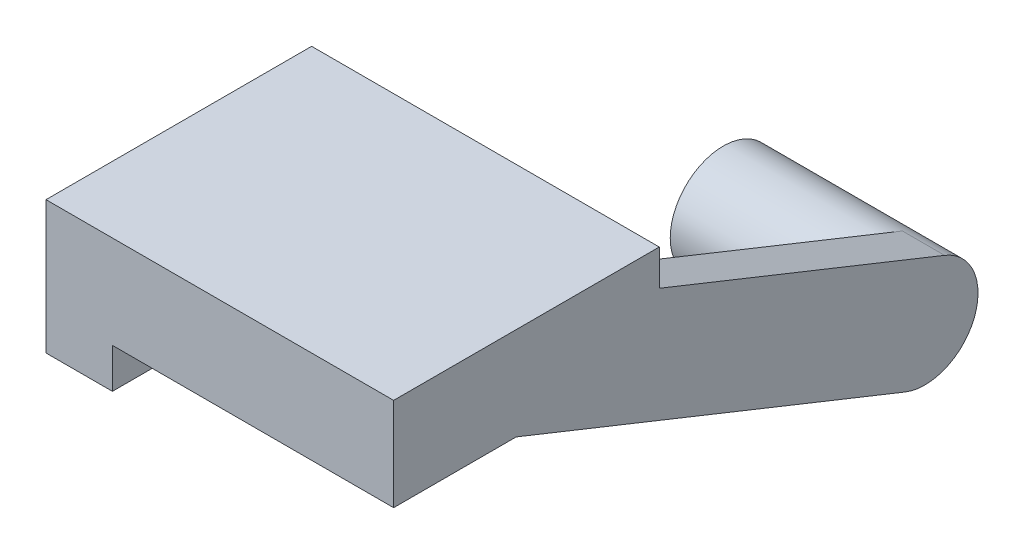
SolidWorks part; units mm, degrees
material "ABS"
ref_plane "Front Plane" through (0, 0, 0) normal (0, 0, 1) x (1, 0, 0)
ref_plane "Top Plane" through (0, 0, 0) normal (0, 1, 0) x (1, 0, 0)
ref_plane "Right Plane" through (0, 0, 0) normal (1, 0, 0) x (0, 0, -1)
sketch "Sketch1" plane through (0, 0, 0) normal (1, 0, 0) x (0, 0, -1)
  line L0 (-5, 0) -> (5, 0) construction
  line L1 (-10, -5) -> (10, -5)
  line L2 (-10, -5) -> (-10, 5)
  line L3 (-10, 5) -> (10, 5)
  line L4 (10, -5) -> (10, 5)
  line L5 (-10, -5) -> (10, 5) construction
  line L6 (-10, 5) -> (10, -5) construction
  circle A0 centre (-5, 0) radius 1.65
  circle A1 centre (5, 0) radius 1.65
  point P0 (0, 0)
  dimension "D1" = 3.3
  dimension "D2" = 10
  dimension "D3" = 20
  dimension "D4" = 10
extrude "Boss-Extrude1" add sketch "Sketch1" along normal blind 5
sketch "Sketch2" plane through (5, 0, 0) normal (1, 0, 0) x (0, 0, -1)
  line L1 (10, -5) -> (10, 5) construction
  line L2 (-10, 5) -> (10, 5)
  line L3 (-10, 5) -> (-10, -2)
  line L4 (-10, -2) -> (10, -2)
  line L13 (10, 5) -> (10, -2)
  line L14 (-10, -5) -> (10, -5) construction
  dimension "D1" = 3
extrude "Boss-Extrude2" add sketch "Sketch2" along normal blind 18
sketch "Sketch3" plane through (23, 0, 0) normal (1, 0, 0) x (0, 0, -1)
  line L0 (10, -2) -> (10, 5) construction
  line L1 (-10, 5) -> (34, 5) construction
  line L2 (-10, 5) -> (-10, -14) construction
  line L3 (-10, -14) -> (34, -14) construction
  line L4 (34, 5) -> (34, -14) construction
  line L5 (-10, 5) -> (10, 5)
  line L6 (-10, 5) -> (-10, -2)
  line L7 (-10, -2) -> (10, -2)
  line L8 (10, 5) -> (10, -2)
  line L9 (10, -5) -> (10, -2) construction
  line L10 (10, -2) -> (30, -10) construction
  line L11 (11.4856, 1.7139) -> (31.4856, -6.2861)
  line L12 (8.5144, -5.7139) -> (28.5144, -13.7139)
  line L13 (-10, -2) -> (10, -2) construction
  line L14 (11.4856, 1.7139) -> (10, 2.3081)
  line L15 (8.5144, -5.7139) -> (-0.7703, -2)
  arc A0 (11.4856, 1.7139) -> (8.5144, -5.7139) centre (10, -2) ccw
  arc A1 (28.5144, -13.7139) -> (31.4856, -6.2861) centre (30, -10) ccw
  point P12 (20, -6)
  line M5 (-10, 5) -> (-10, -2)
  line M6 (-10, -2) -> (10, -2)
  line M7 (10, -2) -> (10, 5)
  line M8 (10, 5) -> (-10, 5)
  dimension "D1" = 19
  dimension "D2" = 44
  dimension "D3" = 8
extrude "Boss-Extrude3" add sketch "Sketch3" along normal blind 3.175 contours A0 L8 M8 M5 M6 | A0 L7 M7 | L12 A1 L11 A0 L7 M7 | A0 L7 L15 | A0 L14 L8
sketch "Sketch4" plane through (23, 0, 0) normal (-1, 0, 0) x (0, 0, 1)
  circle A0 centre (-30, -10) radius 4
  dimension "D2" = 8
extrude "Boss-Extrude4" add sketch "Sketch4" along normal blind 12
